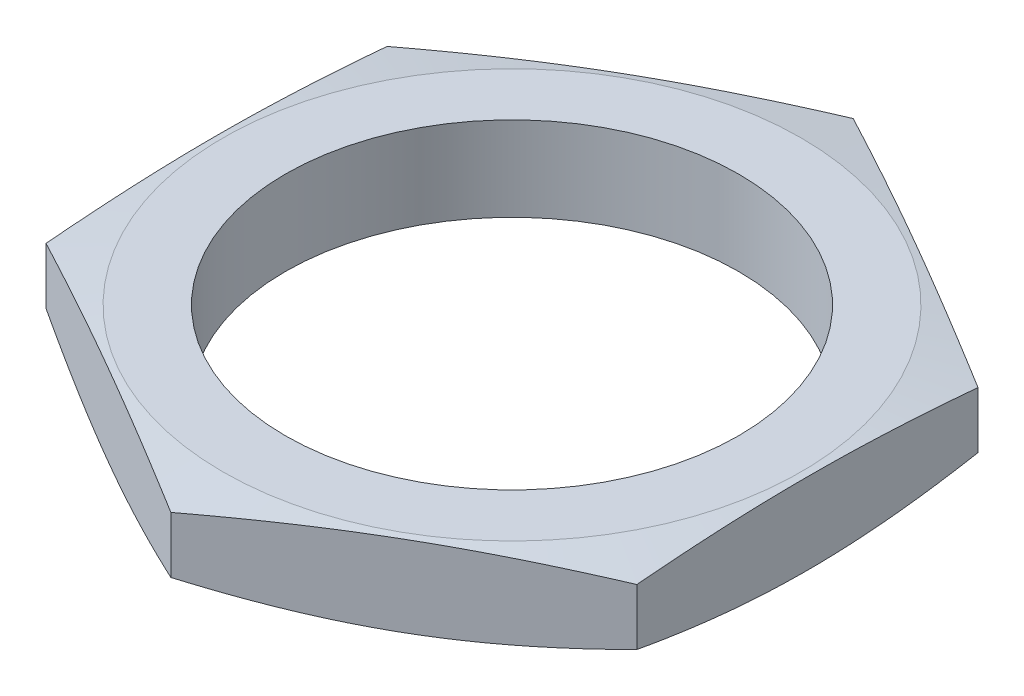
SolidWorks part; units mm, degrees
ref_plane "Alzado" through (0, 0, 0) normal (0, 0, 1) x (1, 0, 0)
ref_plane "Planta" through (0, 0, 0) normal (0, 1, 0) x (1, 0, 0)
ref_plane "Vista lateral" through (0, 0, 0) normal (1, 0, 0) x (0, 0, -1)
sketch "Croquis1" plane through (0, 0, 0) normal (0, 1, 0) x (1, 0, 0)
  line L1 (0, -10.9119) -> (9.45, -5.456)
  line L2 (9.45, -5.456) -> (9.45, 5.456)
  line L3 (9.45, 5.456) -> (0, 10.9119)
  line L4 (0, 10.9119) -> (-9.45, 5.456)
  line L5 (-9.45, 5.456) -> (-9.45, -5.456)
  line L6 (-9.45, -5.456) -> (0, -10.9119)
  circle A0 centre (0, 0) radius 9.45 construction
  dimension "D1" = 18.9
extrude "Saliente-Extruir1" add sketch "Croquis1" along normal blind 2.7
sketch "Croquis2" plane through (0, 2.7, 0) normal (0, 1, 0) x (1, 0, 0)
  circle A0 centre (0, 0) radius 9.25
  dimension "D1" = 18.5
sketch "Croquis3" plane through (0, 0, 0) normal (0, -1, 0) x (-1, 0, 0)
  circle A0 centre (0, 0) radius 9.25
  dimension "D1" = 18.5
extrude "Cortar-Extruir1" cut sketch "Croquis2" against normal blind 2.7 draft 80 flip side to cut
extrude "Cortar-Extruir2" cut sketch "Croquis3" against normal blind 2.7 draft 70 flip side to cut contours A0
hole_wizard "Taladro roscado M16x1.51" positions "Croquis4" profile "Croquis5" tap size "M16x1.5" standard "Ansi Metric"
sketch "Croquis4" plane through (0, 2.7, 0) normal (0, 1, 0) x (1, 0, 0)
  point P0 (0, 0)
sketch "Croquis5" plane through (0, 2.7, 0) normal (1, 0, 0) x (0, 0, 1)
  line L0 (0, 0) -> (0, 43.8562)
  line L1 (0, 43.8562) -> (7.25, 39.5)
  line L2 (7.25, 39.5) -> (7.25, 0)
  line L5 (7.25, 0) -> (0, 0)
  line L10 (0, 43.8562) -> (-7.25, 39.5) construction
  line L11 (0, -6.35) -> (0, 107.95) construction
  dimension "Diámetro de perforador para roscar" = 14.5
  dimension "Profundidad de perforador para roscar" = 39.5
  dimension "Ángulo de perforador" = 118
cosmetic thread "Rosca de taladro1" parameters "D1"=2.7, "D2"=16
